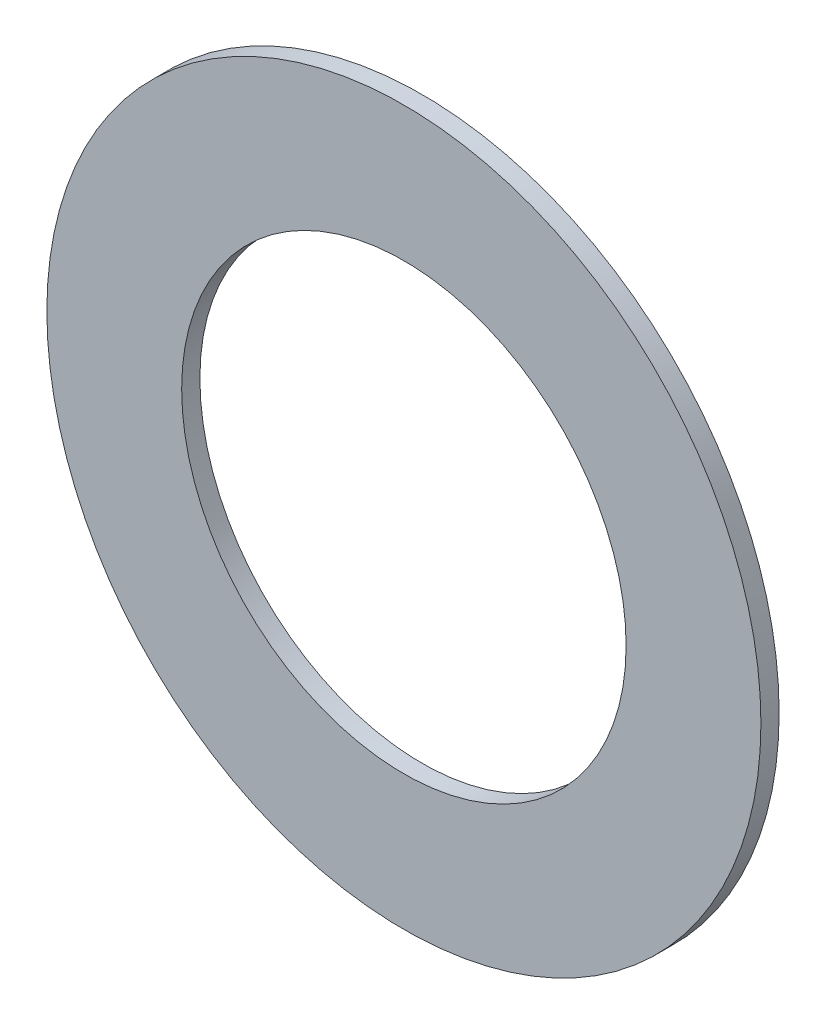
SolidWorks part; units mm, degrees
ref_plane "Plan de face" through (0, 0, 0) normal (0, 0, 1) x (1, 0, 0)
ref_plane "Plan de dessus" through (0, 0, 0) normal (0, 1, 0) x (1, 0, 0)
ref_plane "Plan de droite" through (0, 0, 0) normal (1, 0, 0) x (0, 0, -1)
sketch "Esquisse1" plane through (0, 0, 0) normal (0, 0, 1) x (1, 0, 0)
  circle A0 centre (0, 0) radius 6.1
  circle A1 centre (0, 0) radius 9.8
  dimension "D1" = 12.2
  dimension "D2" = 19.6
extrude "Extrusion1" add sketch "Esquisse1" along normal blind 0.5
